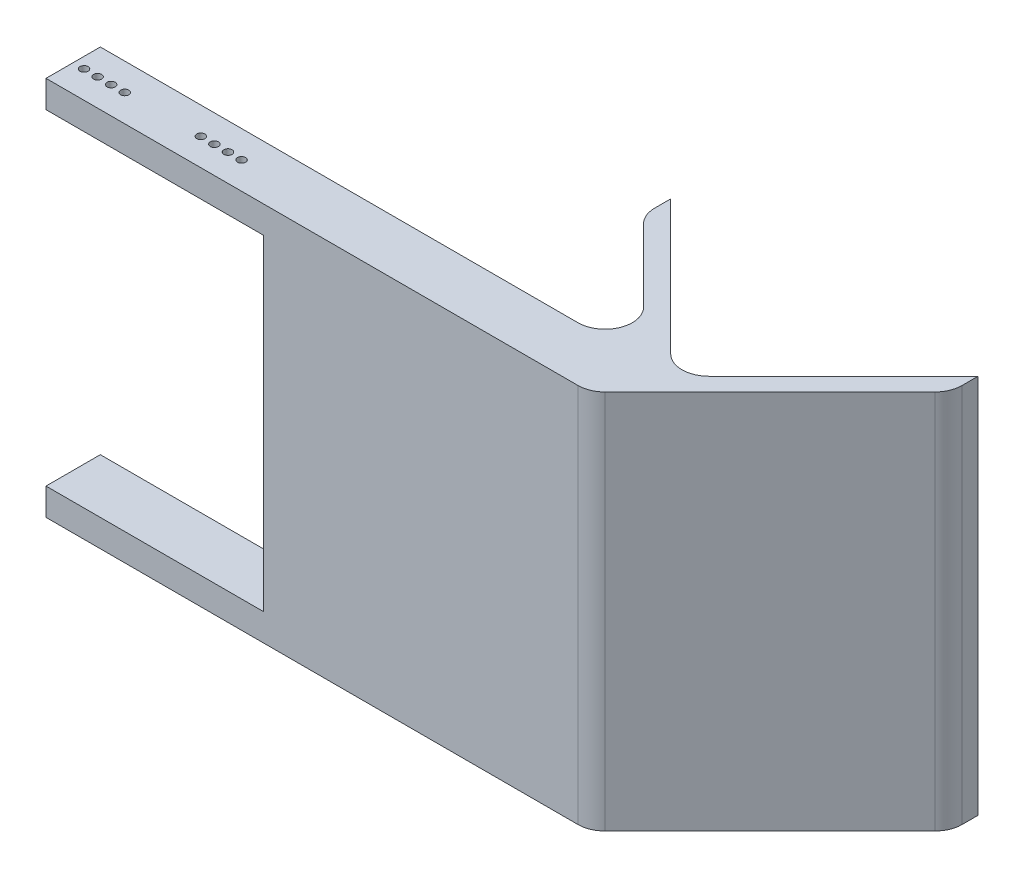
SolidWorks part; units mm, degrees
other "Marquage1"
sketch "Esquisse6" plane through (-75, 0, -38.2843) normal (-0.024, -0.0063, -0.9997) x (-0.9942, -0.1051, 0.0245)
ref_plane "Front Plane" through (0, 0, 0) normal (0, 0, 1) x (1, 0, 0)
ref_plane "Top Plane" through (0, 0, 0) normal (0, 1, 0) x (1, 0, 0)
ref_plane "Right Plane" through (0, 0, 0) normal (1, 0, 0) x (0, 0, -1)
sketch "Sketch1" plane through (0, 0, 0) normal (0, 1, 0) x (1, 0, 0)
  line L0 (-55, 0) -> (55, 0) construction
  line L1 (30, 0) -> (-75, 0)
  line L4 (-75, 0) -> (-75, 10)
  line L5 (30, 10) -> (58.2843, 38.2843)
  line L6 (58.2843, 38.2843) -> (58.2843, 33.2843)
  line L7 (58.2843, 33.2843) -> (35, 10)
  line L8 (30, 10) -> (1.7157, 38.2843)
  line L9 (1.7157, 38.2843) -> (1.7157, 33.2843)
  line L10 (1.7157, 33.2843) -> (25, 10)
  line L11 (35, 10) -> (25, 0)
  line L12 (-75, 10) -> (25, 10)
  line L13 (25, 0) -> (-75, 0)
  dimension "D10" = 10
  dimension "D1" = 30
  dimension "D2" = 30
  dimension "D3" = 75
  dimension "D4" = 10
  dimension "D5" = 33.2843
  dimension "D6" = 58.2843
  dimension "D7" = 225
  dimension "D8" = 33.2843
  dimension "D9" = 28.2843
  dimension "D11" = 90
  dimension "D12" = 45
  dimension "D13" = 5
extrude "Boss-Extrude3" add sketch "Sketch1" along normal blind 70 contours L4 L12 L10 L9 L8 L5 L6 L7 L11 L13
fillet "Fillet7" radius 5 1 edges at (30, 35, -10)
fillet "Fillet8" radius 5 1 edges at (25, 35, -10)
fillet "Fillet9" radius 5 2 edges at (58.2843, 35, -33.2843) (1.7157, 35, -33.2843)
fillet "Fillet10" radius 5 1 edges at (25, 35, 0)
sketch "Esquisse3" plane through (0, 0, -10) normal (0, 0, -1) x (-1, 0, 0)
  line L0 (75, 70) -> (75, 0) construction
  line L1 (75, 5) -> (45, 5)
  line L2 (75, 5) -> (75, 65)
  line L3 (75, 65) -> (45, 65)
  line L4 (45, 5) -> (45, 65)
  line L5 (75, 0) -> (-12.9289, 0) construction
  line L6 (75, 70) -> (-12.9289, 70) construction
  dimension "D1" = 5
  dimension "D2" = 5
  dimension "D3" = 30
extrude "Enlèv. mat.-Extru.1" cut sketch "Esquisse3" against normal through all contours L2 L1 L4 L3
sketch "Esquisse4" plane through (0, 65, 0) normal (0, -1, 0) x (1, 0, 0)
  line L0 (-75, -10) -> (-45, -10) construction
  line L1 (-75, 0) -> (-75, -10) construction
  line L2 (-75, 0) -> (-45, 0) construction
  circle A0 centre (-73, -5) radius 0.75
  circle A1 centre (-68, -5) radius 0.75
  circle A2 centre (-70.5, -5) radius 0.75
  circle A3 centre (-65.5, -5) radius 0.75
  circle A4 centre (-46.5, -5) radius 0.75
  circle A5 centre (-49, -5) radius 0.75
  circle A7 centre (-51.5, -5) radius 0.75
  point P4 (0, 0)
  point P17 (0, 0)
  point P22 (0, 0)
  point P25 (0, 0)
  point P26 (0, 0)
  point P27 (-49.4902, -10)
  point P28 (0, 0)
  point P29 (0, 0)
  point P30 (-46.0122, -5)
  dimension "D1" = 1.5
  dimension "D2" = 5
  dimension "D11" = 5
  dimension "D3" = 2
  dimension "D4" = 2.5
  dimension "D5" = 2.5
  dimension "D6" = 2.5
  dimension "D7" = 5
  dimension "D8" = 5
  dimension "D9" = 5
  dimension "D10" = 14
  dimension "D12" = 10
  dimension "D13" = 2.5
  dimension "D14" = 2.5
sketch "Esquisse5" plane through (0, 0, -10) normal (0, 0, -1) x (-1, 0, 0)
  line L1 (45, 5) -> (35, 5)
  line L2 (45, 5) -> (45, 65)
  line L3 (45, 65) -> (35, 65)
  line L4 (35, 5) -> (35, 65)
  dimension "D1" = 10
extrude "Enlèv. mat.-Extru.2" cut sketch "Esquisse5" against normal through all contours L2 L1 L4 L3
sketch "Esquisse13" plane through (0, 65, 0) normal (0, -1, 0) x (-1, 0, 0)
  line L0 (75, 10) -> (35, 10) construction
  circle A0 centre (44, 5) radius 0.75
  point P2 (43.605, 5.2053)
  dimension "D1" = 2.5
  dimension "D2" = 5
extrude "Enlèv. mat.-Extru.3" cut sketch "Esquisse13" against normal blind 10
extrude "Enlèv. mat.-Extru.6" cut sketch "Esquisse4" against normal blind 10
